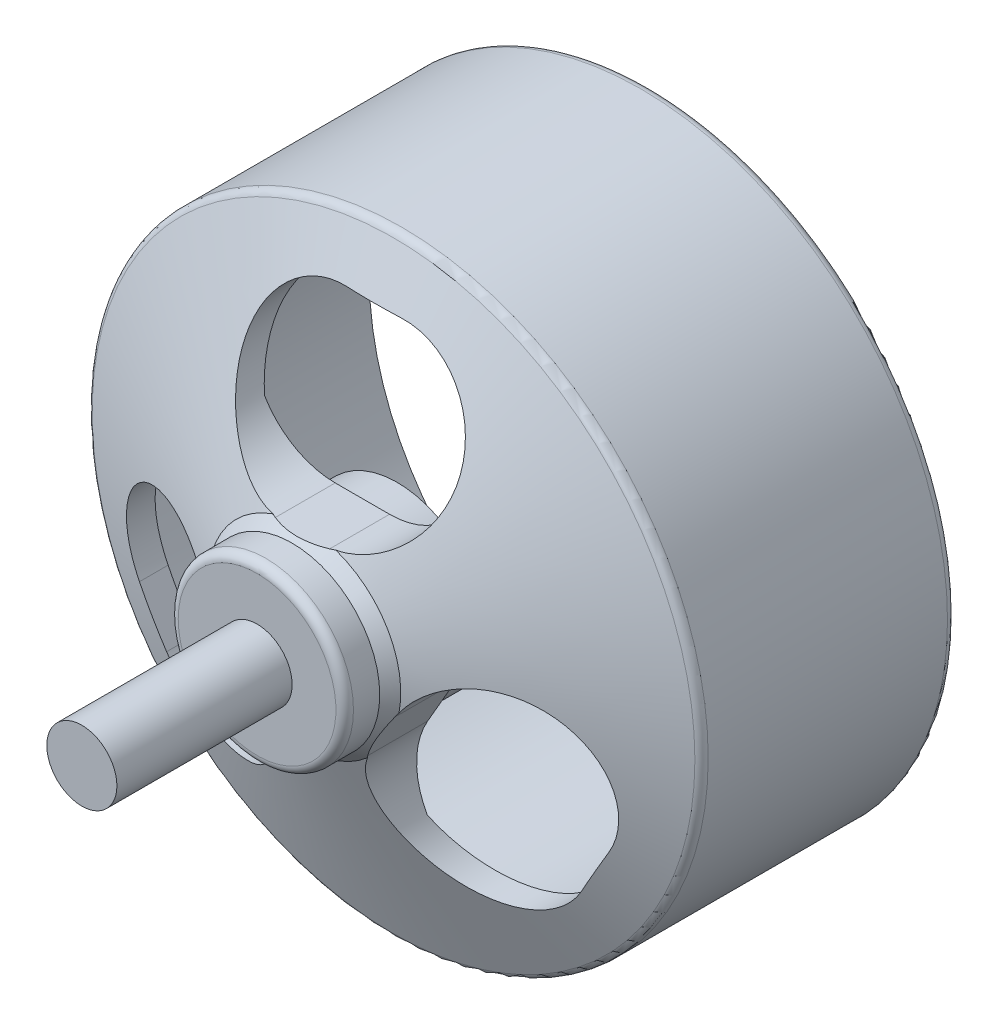
SolidWorks part; units mm, degrees
ref_plane "Спереди" through (0, 0, 0) normal (0, 0, 1) x (1, 0, 0)
ref_plane "Сверху" through (0, 0, 0) normal (0, 1, 0) x (1, 0, 0)
ref_plane "Справа" through (0, 0, 0) normal (1, 0, 0) x (0, 0, -1)
sketch "Эскиз1" plane through (0, 0, 0) normal (1, 0, 0) x (0, 0, -1)
  line L1 (-9, 0) -> (-9, 2)
  line L2 (-9, 2) -> (1, 2)
  line L3 (1, 2) -> (1, 5)
  line L4 (1, 5) -> (3, 5)
  line L5 (3, 5) -> (3.7, 5.5)
  line L6 (3.7, 5.5) -> (8.9165, 17.5)
  line L7 (8.9165, 17.5) -> (23.4, 17.5)
  line L8 (23.4, 17.5) -> (23.4, 16)
  line L9 (23.4, 16) -> (9.9, 16)
  line L10 (9.9, 16) -> (7.0092, 9.35)
  line L11 (7.0092, 9.35) -> (7.0092, 5)
  line L12 (7.0092, 5) -> (9, 5)
  line L13 (9, 5) -> (9, 0)
  line L15 (-9, 0) -> (9, 0)
  line L16 (9, 0) -> (20.1942, 0) construction
  dimension "D1" = 4
  dimension "D2" = 10
  dimension "D3" = 8
  dimension "D4" = 10
  dimension "D5" = 18.7
  dimension "D6" = 1.5
  dimension "D7" = 0.7
  dimension "D8" = 13.5
  dimension "D9" = 22.4
  dimension "D10" = 0.5
  dimension "D11" = 2
  dimension "D12" = 32
  dimension "D13" = 35
revolve "Повернуть1" add sketch "Эскиз1" angle 360 about L16
sketch "Эскиз2" plane through (0, 0, -1) normal (0, 0, 1) x (1, 0, 0)
  line L0 (1.55, 14.5641) -> (-1.55, 14.5641)
  line L1 (1.55, 5.1941) -> (-1.55, 5.1941)
  line L2 (1.55, 9.8791) -> (-1.55, 9.8791) construction
  line L3 (0, 9.8791) -> (0, 0) construction
  circle A0 centre (0, 0) radius 10 construction
  arc A1 (-1.55, 14.5641) -> (-1.55, 5.1941) centre (-1.55, 9.8791) ccw
  arc A2 (1.55, 5.1941) -> (1.55, 14.5641) centre (1.55, 9.8791) ccw
  dimension "D2" = 20
  dimension "D3" = 9.37
  dimension "D1" = 3.1
extrude "Вырез-Вытянуть1" cut sketch "Эскиз2" against normal blind 10
pattern_circular "Круговой массив1" count 3 over 360 about axis through (0, 0, 0) along (0, 0, 1) of "Вырез-Вытянуть1"
fillet "Скругление1" radius 0.5 3 edges at (17.5, 0, -23.4) (17.5, 0, -8.9165) (5, 0, -1)
